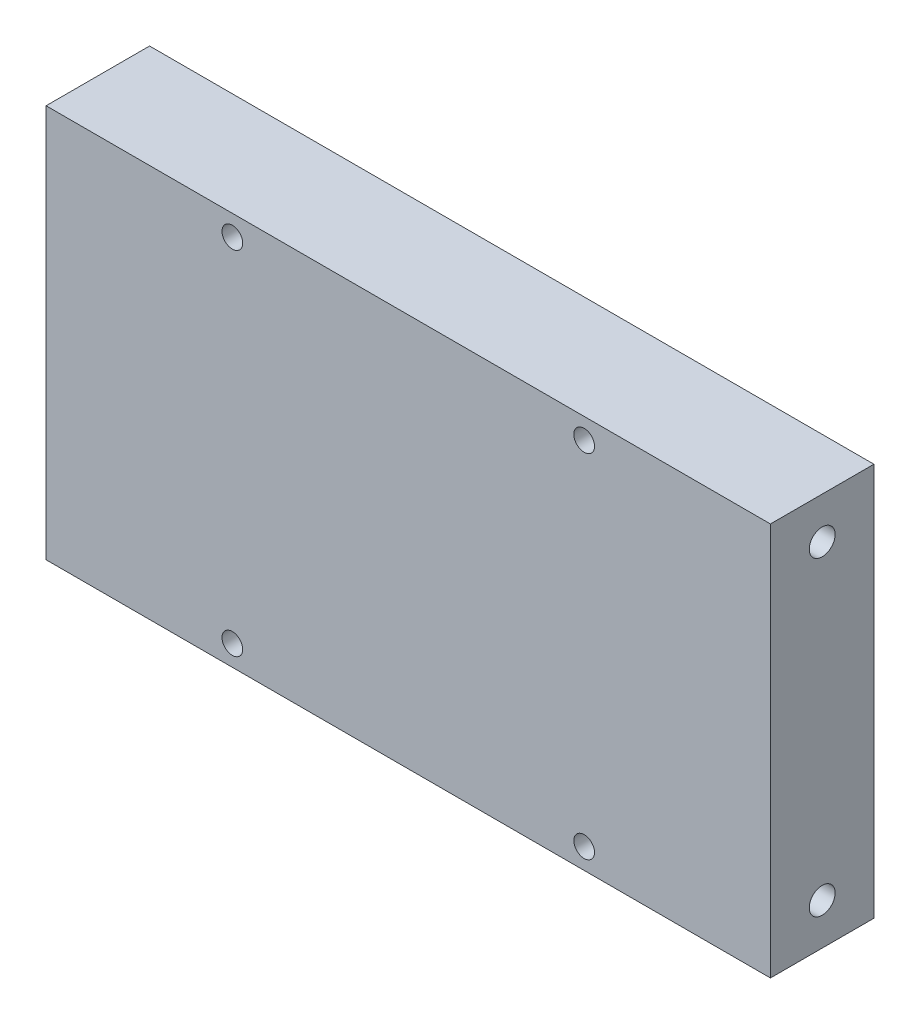
SolidWorks part; units mm, degrees
ref_plane "Front Plane" through (0, 0, 0) normal (0, 0, 1) x (1, 0, 0)
ref_plane "Top Plane" through (0, 0, 0) normal (0, 1, 0) x (1, 0, 0)
ref_plane "Right Plane" through (0, 0, 0) normal (1, 0, 0) x (0, 0, -1)
sketch "Sketch1" plane through (0, 0, 0) normal (0, 0, 1) x (1, 0, 0)
  line L0 (-23.6135, 13.9942) -> (14.3865, -24.0058) construction
  line L1 (14.3865, 13.9942) -> (-23.6135, -24.0058) construction
  line L2 (-39.6135, -36.4058) -> (-39.6135, 16.9942) construction
  line L3 (30.3865, 13.9942) -> (-39.6135, 13.9942)
  line L4 (30.3865, 13.9942) -> (30.3865, -24.0058)
  line L5 (30.3865, -24.0058) -> (-39.6135, -24.0058)
  line L6 (-39.6135, 13.9942) -> (-39.6135, -24.0058)
  line L7 (30.3865, 13.9942) -> (-39.6135, -24.0058) construction
  line L8 (30.3865, -24.0058) -> (-39.6135, 13.9942) construction
  line L9 (14.3865, -24.0058) -> (-23.6135, -24.0058) construction
  circle A0 centre (-21.6135, 11.9942) radius 1
  circle A1 centre (12.3865, 11.9942) radius 1
  circle A2 centre (12.3865, -22.0058) radius 1
  circle A3 centre (-21.6135, -22.0058) radius 1
  point P8 (-4.6135, -5.0058)
  dimension "D1" = 2
extrude "Boss-Extrude1" add sketch "Sketch1" along normal blind 10
sketch "Sketch2" plane through (30.3865, 0, 0) normal (1, 0, 0) x (0, 0, -1)
  line L0 (-5, 13.9942) -> (-5, -24.0058) construction
  line L1 (-10, 13.9942) -> (0, 13.9942) construction
  line L2 (-10, -24.0058) -> (0, -24.0058) construction
  circle A0 centre (-5, 9.9942) radius 1.25
  circle A1 centre (-5, -20.0058) radius 1.25
  dimension "D1" = 2.5
  dimension "D2" = 4
  dimension "D3" = 4
extrude "Cut-Extrude1" cut sketch "Sketch2" against normal blind 12
ref_plane "Plane1" through (-4.6135, 0, 0) normal (-1, 0, 0) x (0, 0, 1)
mirror "Mirror1" about plane through (-4.6135, 0, 0) normal (-1, 0, 0) of "Cut-Extrude1"
